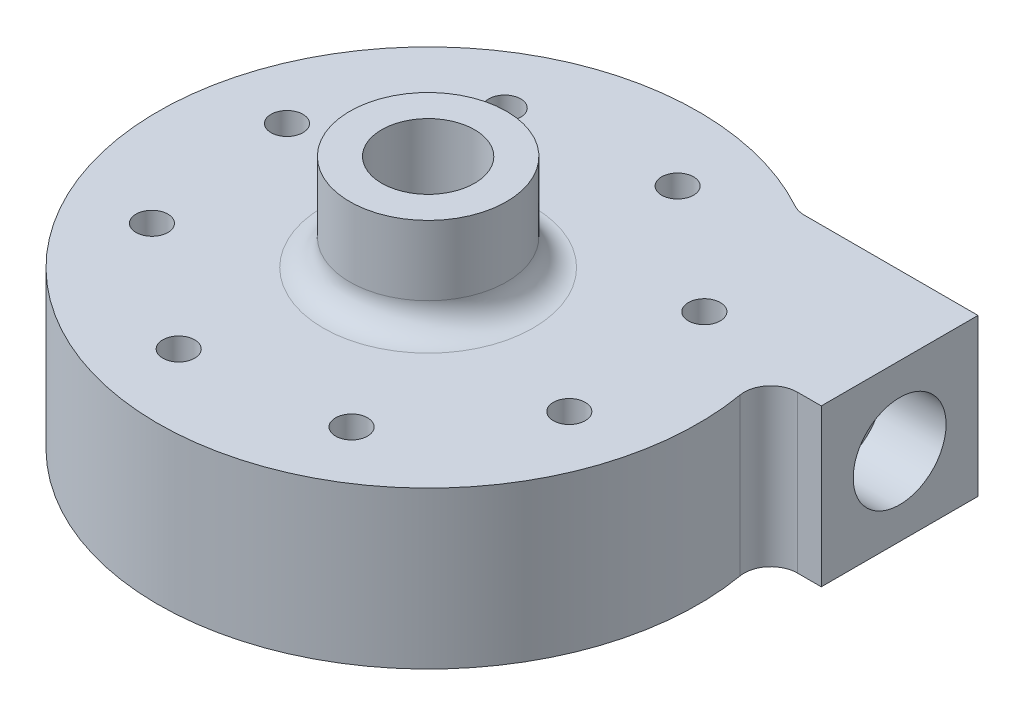
SolidWorks part; units mm, degrees
material "1060 Alloy"
ref_plane "Front" through (0, 0, 0) normal (0, 0, 1) x (1, 0, 0)
ref_plane "Top" through (0, 0, 0) normal (0, 1, 0) x (1, 0, 0)
ref_plane "Right" through (0, 0, 0) normal (1, 0, 0) x (0, 0, -1)
sketch "Sketch1" plane through (0, 0, 0) normal (0, 1, 0) x (1, 0, 0)
  circle A4 centre (0, 0) radius 101.6
  point P0 (0, 0)
  point P17 (0, 0)
  dimension "D1" = 203.2
extrude "body extrusion" add sketch "Sketch1" along normal blind 50.8
sketch "Sketch7" plane through (0, 50.8, 0) normal (0, 1, 0) x (1, 0, 0)
  circle A0 centre (0, 0) radius 8.7313
  dimension "D1" = 17.4625
extrude "inlet tap" cut sketch "Sketch7" against normal blind 20
sketch "Sketch6" plane through (0, 50.8, 0) normal (0, 1, 0) x (1, 0, 0)
  circle A0 centre (0, 0) radius 5.4102
  dimension "D1" = 10.8204
extrude "De" cut sketch "Sketch6" against normal blind 100
sketch "Sketch2" plane through (0, 0, 0) normal (0, 0, 1) x (1, 0, 0)
  line L0 (0, 16.5066) -> (0, 26.8)
  line L1 (0, 26.8) -> (5.4102, 26.8)
  line L2 (5.4102, 26.8) -> (30.6267, 20.2765)
  line L3 (30.6267, 20.2765) -> (30.6267, 16.5066)
  line L4 (30.6267, 16.5066) -> (0, 16.5066) construction
  line L5 (26.6319, 16.5066) -> (26.6319, 21.31) construction
  line L6 (8.7313, 30.8) -> (-8.7313, 30.8) construction
  line L7 (0, 16.5066) -> (0, 0)
  line L8 (0, 0) -> (30.6267, 0)
  line L9 (-101.6, 0) -> (101.6, 0) construction
  line L10 (30.6267, 0) -> (30.6267, 16.5066)
  dimension "D1" = 30.6267
  dimension "D2" = 5.4102
  dimension "D4" = 10.2934
  dimension "D5" = 4
  dimension "D6" = 26.6319
  dimension "D3" = 4.8034
revolve "main chamber" cut sketch "Sketch2" angle 360 about L0
sketch "outlet axis plane ref 1" plane through (0, 0, 0) normal (0, -1, 0) x (1, 0, 0)
  line L0 (0, 0) -> (0, -30.6267) construction
  line L1 (0, -30.6267) -> (93.8828, -38.8404) construction
  line L2 (9.3857, -29.1531) -> (97.3276, -29.1531) construction
  line L3 (9.3857, -29.1531) -> (0, -29.1531) construction
  line L4 (0, -26.6319) -> (98.0474, -26.6319) construction
  circle A0 centre (0, 0) radius 30.6267 construction
  circle A1 centre (0, 0) radius 101.6 construction
  circle A2 centre (0, 0) radius 26.6319 construction
  circle A3 centre (0, 0) radius 101.6 construction
  dimension "D4" = 53.2638
  dimension "D2" = 2.286
  dimension "D3" = 5
  dimension "D1" = 0
sketch "outlet axis plane ref 2" plane through (0, 50.8, 0) normal (0, 1, 0) x (1, 0, 0)
  line L0 (0, 29.1531) -> (97.3276, 29.1531) construction
ref_plane "outlet axial plane" through (0, 0, -29.1531) normal (0, 0, 1) x (1, 0, 0)
sketch "Sketch11" plane through (0, 0, -29.1531) normal (0, 0, 1) x (1, 0, 0)
  line L0 (0, 50.8) -> (0, 0) construction
  line L1 (0, 17.9905) -> (100, 17.9905) construction
  line L2 (0, 19.4554) -> (99.6195, 28.1709)
  line L4 (0, 19.4554) -> (0, 17.9905)
  line L5 (0, 17.9905) -> (99.6195, 17.9905)
  line L6 (99.6195, 17.9905) -> (99.6195, 28.1709)
  line L7 (9.3857, 0) -> (9.3857, 20.2765) construction
  line L8 (9.3857, 0) -> (0, 0) construction
  line L10 (0, 0) -> (93.8828, 0) construction
  line L12 (30.6267, 20.2765) -> (-30.6267, 20.2765) construction
  dimension "D3" = 5
  dimension "D2" = 100
  dimension "D4" = 100
  dimension "D1" = 2.286
revolve "conical outlet" cut sketch "Sketch11" angle 360 about L5
sketch "exit normal plane ref 1" plane through (0, 50.8, 0) normal (0, 1, 0) x (1, 0, 0)
  line L0 (0.098, 30.6265) -> (47.4857, 34.7724) construction
  line L1 (93.8863, 38.8319) -> (0.098, 30.6265) construction
  line L2 (93.8863, 38.8319) -> (0.098, 30.6265) construction
  line L3 (15.6642, 26.3178) -> (99.8161, 18.9555) construction
  line L4 (15.6642, 26.3178) -> (99.6195, 18.9727) construction
  line L5 (15.6642, 26.3178) -> (99.6195, 18.9727) construction
  line L6 (9.3857, 29.1531) -> (97.3276, 29.1531)
  line L7 (47.4857, 29.1531) -> (47.4857, 23.5338)
  line L8 (47.4857, 29.1531) -> (47.4857, 34.7724)
  line L9 (15.6642, 26.3178) -> (99.6195, 18.9727) construction
  circle A0 centre (0, 0) radius 30.6267 construction
  circle A3 centre (0, 0) radius 101.6 construction
  dimension "D1" = 5
  dimension "D2" = 5
  dimension "D3" = 38.1
sketch "exit normal plane ref 2" plane through (0, 0, 0) normal (0, -1, 0) x (1, 0, 0)
  line L0 (47.4857, -23.5338) -> (47.4857, -34.7724)
ref_plane "outlet normal plane" through (47.4857, 0, 0) normal (1, 0, 0) x (0, 0, -1)
sketch "Sketch18" plane through (0, 50.8, 0) normal (0, 1, 0) x (1, 0, 0)
  line L0 (59.4857, 43.8843) -> (26.9065, 43.8843)
  line L1 (47.4857, 29.1531) -> (47.4857, 34.7724) construction
  line L2 (59.4857, 29.1531) -> (59.4857, 43.8843) construction
  line L4 (54.9988, 14.4218) -> (59.4857, 14.4218)
  line L5 (59.4857, 43.8843) -> (59.4857, 14.4218)
  line L6 (-19.2519, 29.1531) -> (19.2519, 29.1531) construction
  arc A0 (24.4955, 44.504) -> (50.0706, 8.5776) centre (0, 0) ccw
  arc A2 (26.9065, 43.8843) -> (24.4955, 44.504) centre (26.9065, 48.8843) cw
  circle A3 centre (0, 0) radius 101.6 construction
  circle A4 centre (0, 0) radius 152.4
  arc A5 (54.9988, 14.4218) -> (50.0706, 8.5776) centre (54.9988, 9.4218) ccw
  dimension "D1" = 101.6
  dimension "D4" = 5
  dimension "D2" = 14.7313
  dimension "D3" = 14.7313
  dimension "D5" = 50.8
  dimension "D6" = 12
extrude "top profile" cut sketch "Sketch18" against normal blind 76.2
sketch "Sketch19" plane through (59.4857, 0, 0) normal (1, 0, 0) x (0, 0, -1)
  line L0 (29.1531, 50.8) -> (29.1531, 17.9905) construction
  line L4 (29.1531, 50.8) -> (34.7724, 50.8) construction
  line L7 (29.1531, 50.8) -> (23.5338, 50.8) construction
  line L10 (14.4218, 50.8) -> (43.8843, 50.8) construction
  circle A1 centre (29.1531, 17.9905) radius 8.7312
  dimension "D1" = 17.4625
extrude "outlet tap" cut sketch "Sketch19" against normal blind 12
sketch "Sketch14" plane through (0, 0, 0) normal (0, 0, 1) x (1, 0, 0)
  line L0 (14.7313, 50.8) -> (14.7313, 32.7218)
  line L3 (14.7313, 32.7218) -> (50.8, 32.7218)
  line L5 (0, 0) -> (0, 3.2593)
  line L6 (-30.6267, 0) -> (30.6267, 0) construction
  line L7 (0, 3.2593) -> (50.8, 3.2593)
  line L8 (50.8, 3.2593) -> (50.8, 0) construction
  line L9 (50.8, 0) -> (0, 0)
  line L10 (59.4857, 26.7218) -> (47.4857, 26.7218) construction
  line L13 (0, 50.8) -> (97.3276, 50.8) construction
  line L14 (14.7313, 50.8) -> (50.8, 50.8)
  line L15 (50.8, 50.8) -> (50.8, 32.7218) construction
  line L16 (8.7313, 30.8) -> (8.7313, 50.8) construction
  line L17 (50.8, 0) -> (50.8, 50.8) construction
  line L19 (50.8, 50.8) -> (127, 50.8)
  line L21 (50.8, 50.8) -> (50.8, 32.7218) construction
  line L22 (50.8, 32.7218) -> (127, 32.7218)
  line L23 (127, 50.8) -> (127, 32.7218)
  line L24 (50.8, 3.2593) -> (127, 3.2593)
  line L25 (50.8, 3.2593) -> (50.8, 0) construction
  line L26 (50.8, 0) -> (127, 0)
  line L27 (127, 3.2593) -> (127, 0)
  dimension "D3" = 6
  dimension "D2" = 6
  dimension "D5" = 76.2
  dimension "D1" = 29.4625
revolve "upper lower cuts" cut sketch "Sketch14" angle 360 about L5
sketch "Sketch20" plane through (0, 32.7218, 0) normal (0, 1, 0) x (1, 0, 0)
  line L1 (15.6642, 26.3178) -> (47.4857, 23.5338) construction
  circle A0 centre (0, 0) radius 38.1 construction
  circle A1 centre (33.1589, 18.7643) radius 3
  dimension "D3" = 6
  dimension "D2" = 6
  dimension "D1" = 76.2
extrude "bolts" cut sketch "Sketch20" against normal blind 76.2
pattern_circular "bolt pattern" count 8 over 360 about axis through (0, 0, 0) along (0, 1, 0) of "bolts"
fillet "inlet fillet" radius 5 1 edges at (0, 32.7218, -14.7313)
equation "\"de\" = 0.426in \t\t\t\t'entrance eye diameter"
equation "\"D1@body extrusion\"=2in"
equation "\"D2@Sketch2\"=\"de\"/2"
equation "\"D3@Sketch2\"=\"impeller cavity outer height\""
equation "\"D1@Sketch2\"=\"impeller cavity diameter\"/2"
equation "\"D1@Sketch6\"=\"de\""
equation "\"D1@De\" = 100mm"
equation "\"D1@Sketch7\"=\"impeller housing threaded inlet diameter\""
equation "\"D1@inlet tap\" = \"impeller housing threaded inlet depth\""
equation "\"D4@Sketch2\"=\"impeller cavity center height\""
equation "\"z\" = 8 \t\t\t\t'number of blades"
equation "\"d2\" = 2.097in \t\t\t\t'outer diameter of the impeller "
equation "\"d_exit\" = 0.18in \t\t\t'volute throat aka D4"
equation "\"theta\" = 15"
equation "\"b2\" = .071in\t\t\t\t\t\t\t\t'tip height from disc surface at d2"
equation "\"b1\" = \"b2\" + (\"d2\"/2 - \"de\"/2)*sin(\"theta\")\t\t\t\t'tip height from disc surface at inlet eye"
equation "\"s\" = ( 1/\"z\")*(3.14*\"de\" - (3.14*(\"de\"^2) / (4*(\"b1\"))))\t\t'thickness of blades, calculated from area"
equation "\"s_opening\" = (3.14*\"de\" - \"z\"*\"s\")/\"z\"\t\t\t\t\t'ideal gap between blades, calculated from area"
equation "\"area_eye\"=3.14*(\"de\"^2)/4\t\t\t\t\t\t'eye area"
equation "\"single_channel_area\"=\"s_opening\"*\"b1\"\t\t\t\t\t'ideal area between two blades"
equation "\"impeller upper clearance\"= .5mm"
equation "\"impeller horizontal clearance\"= (\"d2\"*1.15 - \"d2\")/2 \t\t\t\t\t'clearance based on D2-D3 ratio for circular volute, ranges 1.15 to 1.2"
equation "\"impeller bottom clearance\"= .5mm"
equation "\"impeller base thickness\"= 2mm"
equation "\"impeller boss depth\" = \"shaft impeller section length\" + 3mm + \"impeller bolt head depth\" - \"impeller base thickness\""
equation "\"impeller cavity center height\"= \"impeller bottom clearance\" + \"impeller upper clearance\" + \"final impeller center height\""
equation "\"impeller cavity diameter\"= 2 * \"impeller horizontal clearance\" + \"d2\" \t\t\t'called D3 analytically"
equation "\"impeller cavity outer height\"= \"impeller bottom clearance\" + \"impeller upper clearance\" + \"impeller base thickness\" + \"b2\" \t\t\t'this is height at impeller diameter d2, not at d3"
equation "\"impeller housing bolt count\" = 8"
equation "\"impeller housing bolt diameter\" = 6mm"
equation "\"impeller housing bolt pattern diameter\" = 3in"
equation "\"impeller housing o-ring channel height\"= 1.5mm"
equation "\"impeller housing o ring channel width\"= 1.5mm"
equation "\"impeller housing o-ring diameter\" = 2in"
equation "\"impeller housing threaded inlet diameter\" = 0.6875in \t\t\t'this is the 11/16 drill size for 1/2 npt fitting"
equation "\"impeller housing threaded inlet depth\"= 20mm"
equation "\"impeller housing thickness\"= \"impeller housing exit threaded diameter\" + 2*\"impeller housing outlet purchase\""
equation "\"impeller housing exit threaded diameter\"= 0.6875in \t\t\t'this is the 11/16 drill size for 1/2 npt fitting"
equation "\"impeller housing exit threaded depth\"= 12mm"
equation "\"impeller housing diameter\" = 4in"
equation "\"impeller housing diffuser conical angle\"=10"
equation "\"impeller housing diffuser tangent angle\"=0"
equation "\"motor to housing distance\" = \"motor shaft pride\" + \"shaft coupler section length\" - \"bearing plate bearing stop depth\" + 2mm"
equation "\"D2@outlet axis plane ref 1\" = \"d_exit\" / 2"
equation "\"D3@outlet axis plane ref 1\" = \"impeller housing diffuser conical angle\" / 2"
equation "\"D1@Sketch11\"=\"d_exit\"/2"
equation "\"D3@Sketch11\"=\"impeller housing diffuser conical angle\"/2"
equation "\"D1@exit normal plane ref 1\"=\"impeller housing diffuser conical angle\" / 2"
equation "\"impeller housing outlet purchase\" = 6mm"
equation "\"D1@Sketch14\"=\"impeller housing thickness\""
equation "\"bearing OD\" = 30mm"
equation "\"bearing outer race thickness\"= 1mm"
equation "\"bearing ID\"= 10mm"
equation "\"bearing depth\"= 9mm"
equation "\"bearing inner race thickness\"= 1mm"
equation "\"small seal OD\" = 20mm"
equation "\"small seal ID\"= 8mm"
equation "\"small seal depth\" = 8.3mm"
equation "\"big seal OD\" = 27mm"
equation "\"big seal ID\"= 15mm"
equation "\"big seal depth\"= 8.3mm"
equation "\"inlet area before cut\" = \"minimum channel width\" * (\"z\") * \"b1\"\t\t\t\t'if minimum channel width>s_opening, this is larger than area_eye"
equation "\"area to cut\" = \"inlet area before cut\" - \"area_eye\"\t\t\t\t\t\t'amount of extra area\t\t\t\t\t"
equation "\"height to cut\" = \"area to cut\" / ((\"z\")* \"minimum channel width\")+ .0001in\t\t\t'the 0.0001 in cut is to avoid errors in model"
equation "\"final impeller center height\" = \"impeller base thickness\" + \"b1\" - \"height to cut\"\t\t'corrected height so that sum of channel areas equals eye area"
equation "\"bearing bore\" = \"bearing depth\" + 1mm"
equation "\"small seal bore\" = \"small seal depth\" + 1mm"
equation "\"big seal bore\" = \"big seal depth\" + 1mm"
equation "\"impeller boss diameter\" = \"big seal ID\""
equation "\"impeller dowel diameter\" = 2mm"
equation "\"impeller bolt head diameter\" = 7.5mm"
equation "\"impeller bolt head depth\" = 4mm"
equation "\"impeller shaft bore\"= 8mm"
equation "\"impeller shaft bore depth\" = \"impeller boss depth\" + \"impeller base thickness\" - \"impeller bolt head depth\" - 3mm"
equation "\"impeller dowel length\" = 2mm*2 + \"impeller shaft bore\""
equation "\"impeller screw hole bore\" = 4mm"
equation "\"shaft impeller screw hole diameter\" = \"impeller screw hole bore\""
equation "\"shaft impeller section length\" = \"big seal plate thickness\"/2 + \"impeller bottom clearance\" + \"impeller base thickness\" - \"impeller bolt head depth\" - 3mm"
equation "\"shaft impeller screw hole depth\" = \"shaft impeller section length\"-\"impeller dowel diameter\"-2mm"
equation "\"shaft impeller section diameter\" = \"impeller shaft bore\""
equation "\"shaft seal section diameter\"=\"small seal ID\""
equation "\"shaft seal section length\"= \"big seal plate thickness\"/2 + \"small seal bore\" + 2mm"
equation "\"shaft bearing section diameter\" = \"bearing ID\""
equation "\"shaft bearing section length\" = \"bearing bore\""
equation "\"shaft bearing stop diameter\" = \"bearing ID\" + 2mm"
equation "\"shaft bearing stop length\" = 2mm"
equation "\"shaft coupler section diameter\" = 8mm"
equation "\"shaft coupler section length\" = \"shaft bearing stop length\" + \"coupler length\"/2 + 4mm"
equation "\"coupler motor shaft hole ID\"= 8mm"
equation "\"coupler OD\"= 17mm"
equation "\"coupler length\"= 25mm"
equation "\"square plate diameter\" = 3in"
equation "\"square plate bolt pattern diameter\"= 2in"
equation "\"square plate bolt hole ID\" = 8mm"
equation "\"bearing plate bearing stop ID\" = \"bearing OD\" - 4mm"
equation "\"bearing plate bearing stop depth\" = 3mm"
equation "\"bearing plate thickness\" = \"bearing bore\" + \"bearing plate bearing stop depth\""
equation "\"small seal plate lip depth\" = \"shaft bearing stop length\" + 1mm"
equation "\"small seal plate lip ID\" = \"small seal OD\" - 3mm"
equation "\"small seal plate thickness\" = \"small seal plate lip depth\" + \"small seal bore\""
equation "\"big seal plate lip depth\" = 8mm"
equation "\"big seal plate thickness\" = \"big seal plate outer thickness\" + \"big seal plate riser height\""
equation "\"big seal plate pressure hole diameter\" = .125in\t\t\t'this is 1/8 drill "
equation "\"big seal plate pressure tap diameter\" = .328125in \t\t'this is 21/64 drill for a 1/8 ANPT tap"
equation "\"big seal plate pressure tap depth\" = 9mm"
equation "\"motor mount coupler hole diameter\"= \"coupler OD\"+ 4mm"
equation "\"motor mount to housing post radius\"= ( 3 * \"square plate bolt hole ID\" ) / 2"
equation "\"motor mount m4 screw hole diameter\"= 4mm"
equation "\"motor mount m4 head diameter\"= 7.25mm"
equation "\"motor mount m4 head depth\"= 4mm"
equation "\"motor mount m4 pattern diamater\" = 30mm"
equation "\"motor mount plate thickness\"= 8mm + \"motor mount m4 head depth\""
equation "\"motor shaft pride\"= 32mm"
equation "\"motor shaft flat section length from tip\"= 25.7mm"
equation "\"motor shaft bore end clearance\"= 2mm"
equation "\"coupler shaft to motor clearance\" = 2mm"
equation "\"motor mount shaft hole depth\"= \"motor shaft pride\""
equation "\"D1@Sketch18\"=\"impeller housing diameter\""
equation "\"D2@Sketch18\"=\"impeller housing exit threaded diameter\"/2 + \"impeller housing outlet purchase\""
equation "\"D3@Sketch18\"=\"impeller housing exit threaded diameter\"/2  + \"impeller housing outlet purchase\""
equation "\"D1@Sketch19\"=\"impeller housing exit threaded diameter\""
equation "\"D1@outlet tap\" = \"impeller housing exit threaded depth\""
equation "\"D1@Sketch20\"=\"impeller housing bolt pattern diameter\" "
equation "\"D2@Sketch20\"=\"impeller housing bolt diameter\""
equation "\"D3@Sketch20\"=\"impeller housing bolt diameter\""
equation "\"D1@bolt pattern\" = \"impeller housing bolt count\""
equation "\"D2@exit normal plane ref 1\"=\"impeller housing diffuser conical angle\" / 2"
equation "\"impeller housing diffuser length\" = 1.5in"
equation "\"D3@exit normal plane ref 1\"=\"impeller housing diffuser length\""
equation "\"D6@Sketch18\"=\"impeller housing exit threaded depth\""
equation "\"D4@outlet axis plane ref 1\"=\"d2\""
equation "\"D2@Sketch14\"=\"impeller housing outlet purchase\""
equation "\"minimum channel width\" = \"s_opening\"\t\t\t\t\t\t\t\t'minimum s, set this to a bit size for milling or to s_opening for DMLS"
equation "\"big seal plate outer thickness\" = \"big seal plate pressure tap diameter\" + (\"impeller housing outlet purchase\"-2mm)*2"
equation "\"D6@Sketch2\"=\"d2\"/2"
equation "\"big seal plate riser height\" = 13.25mm\t\t'this is a reference dimension that needs to be taken from the impeller housing drawing"
